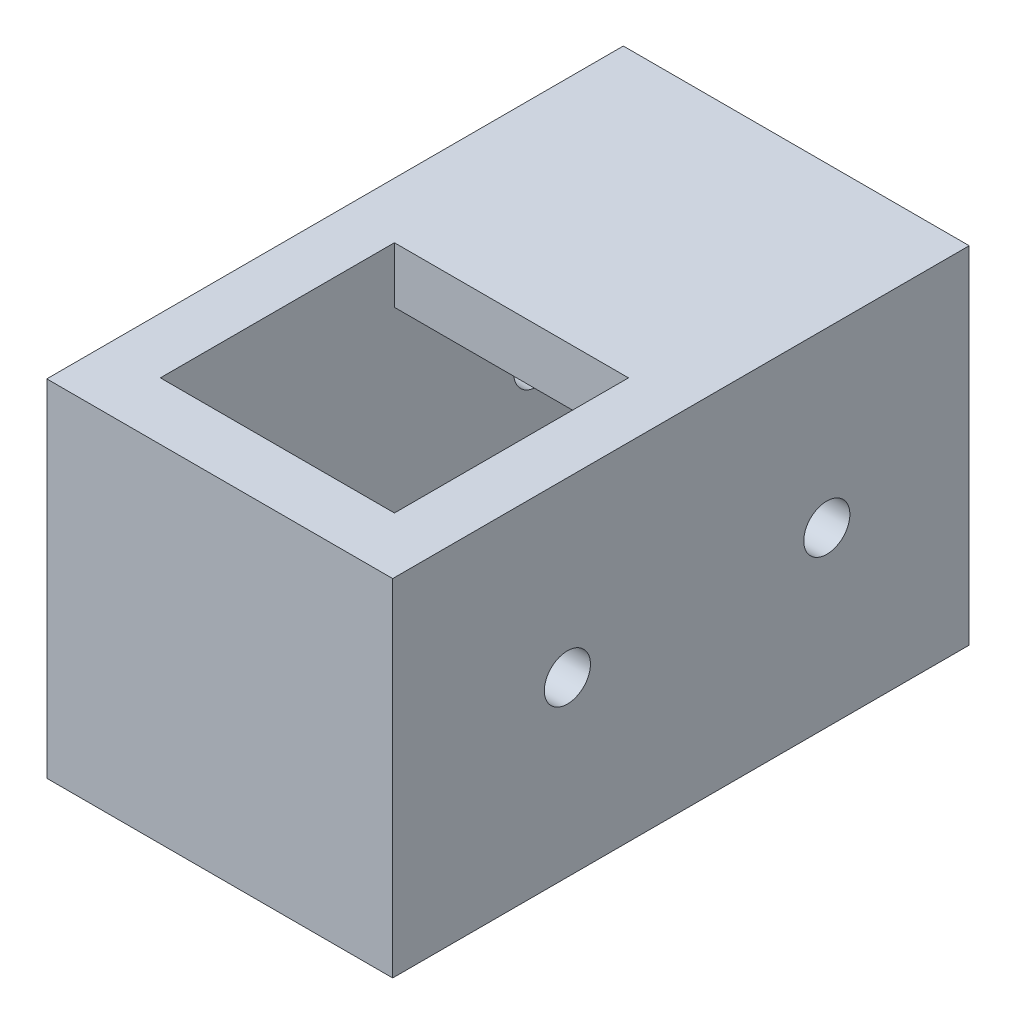
SolidWorks part; units mm, degrees
ref_plane "Front Plane" through (0, 0, 0) normal (0, 0, 1) x (1, 0, 0)
ref_plane "Top Plane" through (0, 0, 0) normal (0, 1, 0) x (1, 0, 0)
ref_plane "Right Plane" through (0, 0, 0) normal (1, 0, 0) x (0, 0, -1)
sketch "Sketch1" plane through (0, 0, 0) normal (0, 0, 1) x (1, 0, 0)
  line L1 (0, 0) -> (30, 0)
  line L2 (0, 0) -> (0, 30)
  line L3 (0, 30) -> (30, 30)
  line L4 (30, 0) -> (30, 30)
  dimension "D1" = 30
extrude "Boss-Extrude1" add sketch "Sketch1" along normal blind 50
sketch "Sketch2" plane through (0, 0, 0) normal (0, 0, -1) x (-1, 0, 0)
  line L1 (-25.15, 25.15) -> (-4.85, 25.15)
  line L2 (-25.15, 25.15) -> (-25.15, 4.85)
  line L3 (-25.15, 4.85) -> (-4.85, 4.85)
  line L4 (-4.85, 25.15) -> (-4.85, 4.85)
  line L5 (-15, 25.15) -> (-15, 4.85) construction
  line L6 (-30, 0) -> (-30, 30) construction
  line L7 (0, 30) -> (0, 0) construction
  line L8 (-25.15, 15) -> (-4.85, 15) construction
  line L11 (0, 0) -> (-30, 0) construction
  line L12 (-30, 30) -> (0, 30) construction
  dimension "D1" = 20.3
sketch "Sketch3" plane through (0, 30, 0) normal (0, 1, 0) x (1, 0, 0)
  line L0 (15, -24.7) -> (15, -45) construction
  line L1 (4.85, -24.7) -> (25.15, -24.7)
  line L2 (4.85, -24.7) -> (4.85, -45)
  line L3 (4.85, -45) -> (25.15, -45)
  line L4 (25.15, -24.7) -> (25.15, -45)
  line L5 (0, -50) -> (0, 0) construction
  line L6 (30, -50) -> (30, 0) construction
  line L7 (30, -50) -> (0, -50) construction
  dimension "D1" = 20.3
  dimension "D2" = 5
extrude "Cut-Extrude1" cut sketch "Sketch3" against normal through all
extrude "Cut-Extrude2" cut sketch "Sketch2" against normal blind 30 contours L2 L3 L4 L1
sketch "Sketch5" plane through (0, 0, 0) normal (-1, 0, 0) x (0, 0, 1)
  line L0 (24.7, 30) -> (45, 30) construction
  line L1 (24.7, 30) -> (45, 30)
  line L2 (34.85, 30) -> (34.85, 0) construction
  line L3 (50, 0) -> (0, 0) construction
  line L4 (24.7, 25.15) -> (0, 25.15) construction
  line L5 (24.7, 25.15) -> (0, 25.15)
  circle A0 centre (34.85, 15) radius 2
  circle A1 centre (12.35, 15) radius 2
  point P8 (0, 0)
  point P13 (12.35, 25.15)
  dimension "D1" = 4
extrude "Cut-Extrude3" cut sketch "Sketch5" against normal through all contours A0 | A1
